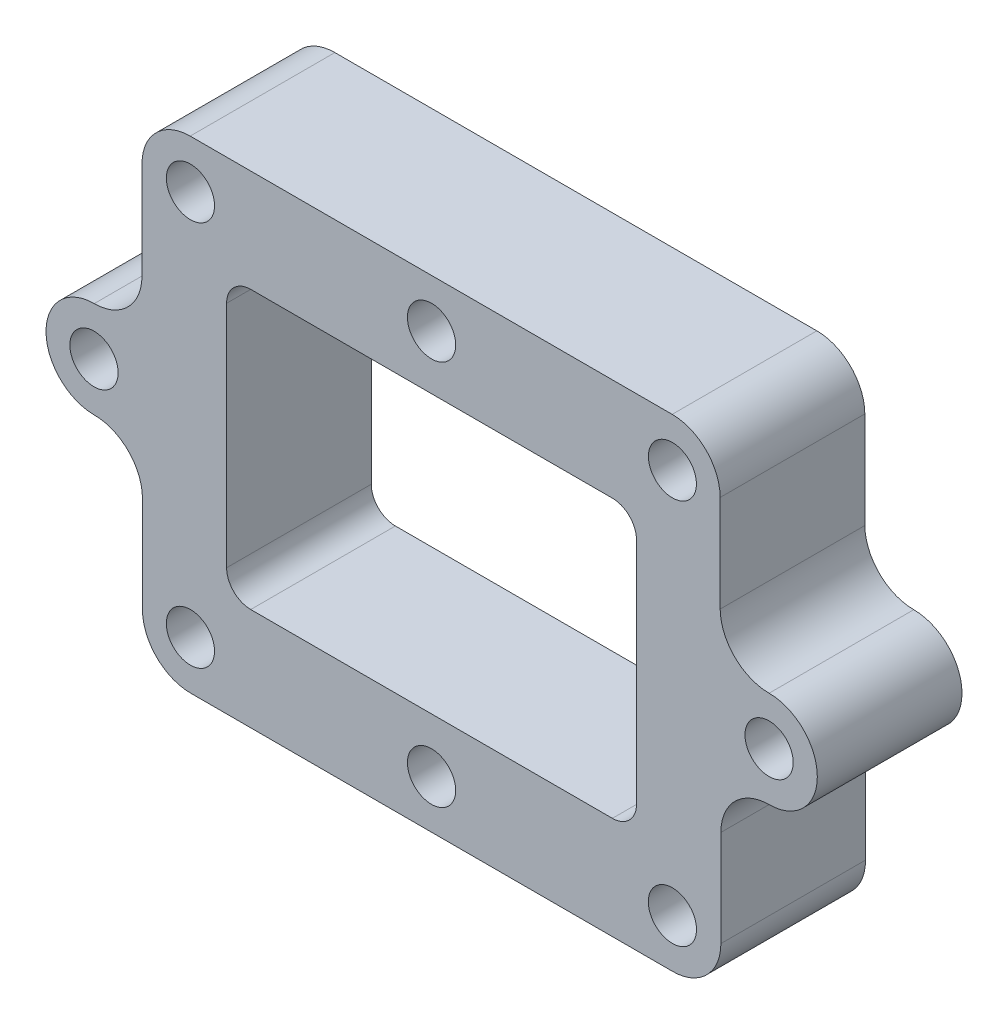
SolidWorks part; units mm, degrees
ref_plane "Front Plane" through (0, 0, 0) normal (0, 0, 1) x (1, 0, 0)
ref_plane "Top Plane" through (0, 0, 0) normal (0, 1, 0) x (1, 0, 0)
ref_plane "Right Plane" through (0, 0, 0) normal (1, 0, 0) x (0, 0, -1)
sketch "Sketch1" plane through (0, 0, 0) normal (0, 0, 1) x (1, 0, 0)
  line L0 (25.4633, -63.5) -> (152.4, -63.5)
  line L1 (25.3367, 63.5) -> (152.2734, 63.5)
  line L2 (12.7633, -50.8) -> (12.7633, -25.4421)
  line L3 (165.1, -50.8) -> (165.1, -25.4421)
  line L4 (12.6367, 50.8) -> (12.6367, 25.4067)
  line L5 (164.9101, 50.8633) -> (164.9101, 25.4067)
  line L6 (34.925, 30.1625) -> (34.925, -30.1625)
  line L7 (142.875, 30.1625) -> (142.875, -30.1625)
  line L8 (41.275, 36.5125) -> (136.525, 36.5125)
  line L9 (41.275, -36.5125) -> (136.525, -36.5125)
  circle A0 centre (0, 0) radius 6.35
  circle A1 centre (177.8, 0) radius 6.35
  circle A2 centre (88.9, 50.8) radius 6.35
  circle A3 centre (88.9, -50.8) radius 6.35
  circle A4 centre (152.3367, 50.8) radius 6.3219
  circle A5 centre (25.4, 50.8) radius 6.35
  circle A6 centre (25.4, -50.8) radius 6.35
  circle A7 centre (152.3367, -50.8) radius 6.35
  arc A8 (152.4, -63.5) -> (165.1, -50.8) centre (152.4, -50.8) ccw
  arc A9 (25.4633, -63.5) -> (12.7633, -50.8) centre (25.4633, -50.8) cw
  arc A10 (25.3367, 63.5) -> (12.6367, 50.8) centre (25.3367, 50.8) ccw
  arc A11 (152.2734, 63.5) -> (164.9101, 50.8633) centre (152.2734, 50.8633) cw
  arc A12 (12.7633, -25.4421) -> (0.0633, -12.7421) centre (0.0633, -25.4421) ccw
  arc A13 (0.0633, -12.7421) -> (0.0633, 12.6579) centre (0.0633, -0.0421) cw
  arc A14 (165.1, -25.4421) -> (177.8, -12.7421) centre (177.8, -25.4421) cw
  arc A15 (177.8, -12.7421) -> (177.8, 12.6579) centre (177.8, -0.0421) ccw
  arc A16 (0.0633, 12.6579) -> (12.6367, 25.4067) centre (0.0633, 25.2326) ccw
  arc A17 (177.8, 12.6579) -> (164.9101, 25.4067) centre (177.8, 25.5486) cw
  arc A18 (34.925, 30.1625) -> (41.275, 36.5125) centre (41.275, 30.1625) cw
  arc A19 (34.925, -30.1625) -> (41.275, -36.5125) centre (41.275, -30.1625) ccw
  arc A20 (142.875, 30.1625) -> (136.525, 36.5125) centre (136.525, 30.1625) ccw
  arc A21 (142.875, -30.1625) -> (136.525, -36.5125) centre (136.525, -30.1625) cw
  point P55 (0, 0)
  dimension "D1" = 12.7
  dimension "D2" = 12.7
  dimension "D4" = 12.7
  dimension "D5" = 12.7
  dimension "D6" = 12.7
  dimension "D7" = 12.7
  dimension "D8" = 12.7
  dimension "D9" = 12.6438
  dimension "D23" = 12.7
  dimension "D24" = 12.7
  dimension "D29" = 12.6367
  dimension "D30" = 12.7
  dimension "D28" = 12.7
  dimension "D32" = 12.7
  dimension "D33" = 12.7
  dimension "D34" = 12.7
  dimension "D35" = 12.6367
  dimension "D38" = 6.35
  dimension "D39" = 6.35
  dimension "D40" = 6.35
  dimension "D41" = 6.35
  dimension "D3" = 177.8
  dimension "D10" = 63.4367
  dimension "D11" = 63.4367
  dimension "D12" = 101.6
  dimension "D13" = 63.5
  dimension "D14" = 63.5
  dimension "D15" = 101.6
  dimension "D16" = 88.9
  dimension "D17" = 88.9
  dimension "D18" = 50.8
  dimension "D19" = 101.6
  dimension "D20" = 88.9
  dimension "D21" = 50.8
  dimension "D22" = 50.8
  dimension "D25" = 127
  dimension "D26" = 127
  dimension "D27" = 12.7
  dimension "D31" = 12.7
  dimension "D36" = 107.95
  dimension "D42" = 73.025
extrude "Boss-Extrude1" add sketch "Sketch1" along normal blind 38.1
